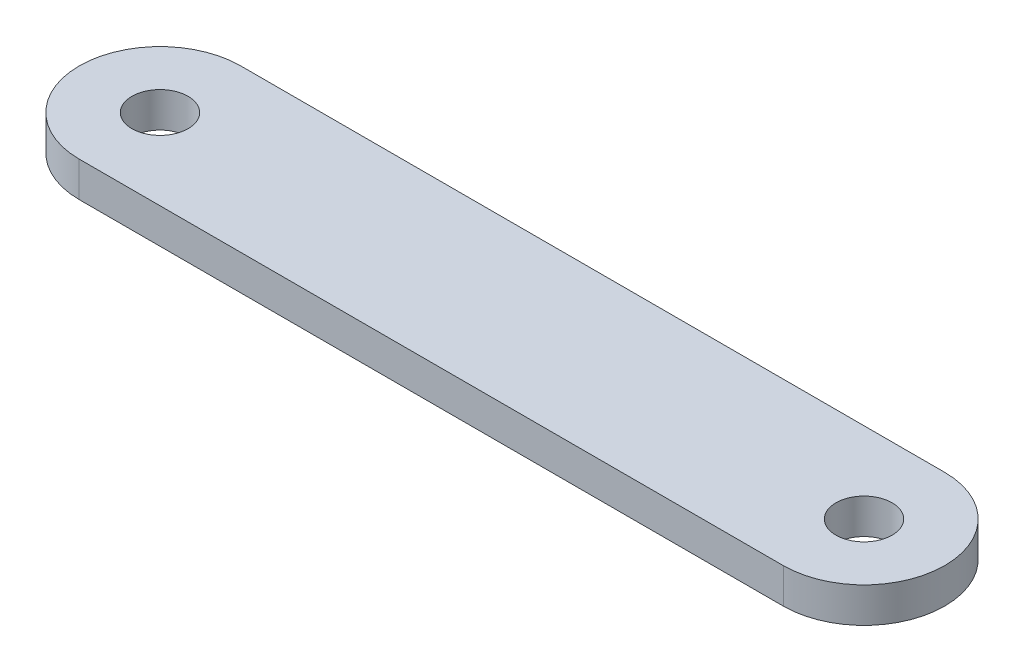
SolidWorks part; units mm, degrees
ref_plane "Front Plane" through (0, 0, 0) normal (0, 0, 1) x (1, 0, 0)
ref_plane "Top Plane" through (0, 0, 0) normal (0, 1, 0) x (1, 0, 0)
ref_plane "Right Plane" through (0, 0, 0) normal (1, 0, 0) x (0, 0, -1)
sketch "Sketch1" plane through (0, 0, 0) normal (0, 1, 0) x (1, 0, 0)
  line L1 (-9.4939, 1.0695) -> (30.6161, 1.0695)
  line L2 (-9.4939, 1.0695) -> (-9.4939, 5.6695)
  line L3 (-9.4939, 5.6695) -> (30.6161, 5.6695)
  line L4 (30.6161, 1.0695) -> (30.6161, 5.6695)
  line L5 (-9.4939, 1.0695) -> (30.6161, 1.0695)
  line L6 (-9.4939, 1.0695) -> (-9.4939, -3.5305)
  line L7 (-9.4939, -3.5305) -> (30.6161, -3.5305)
  line L8 (30.6161, 1.0695) -> (30.6161, -3.5305)
  circle A0 centre (-9.4939, 1.0695) radius 1.6
  circle A1 centre (30.6161, 1.0695) radius 1.6
  circle A2 centre (-9.4939, 1.0695) radius 4.6
  circle A3 centre (30.6161, 1.0695) radius 4.6
  dimension "D1" = 3.2
  dimension "D2" = 3.2
  dimension "D3" = 40.11
  dimension "D4" = 3
extrude "Boss-Extrude1" add sketch "Sketch1" against normal blind 2 contours L5 A2 L2 A0 | L2 A2 L6 A0 | L6 A2 L5 A0 | A3 L1 A2 L7 | A3 L3 A2 L1 | L5 A3 L8 A1 | L4 A3 L5 A1 | L8 A3 L4 A1
